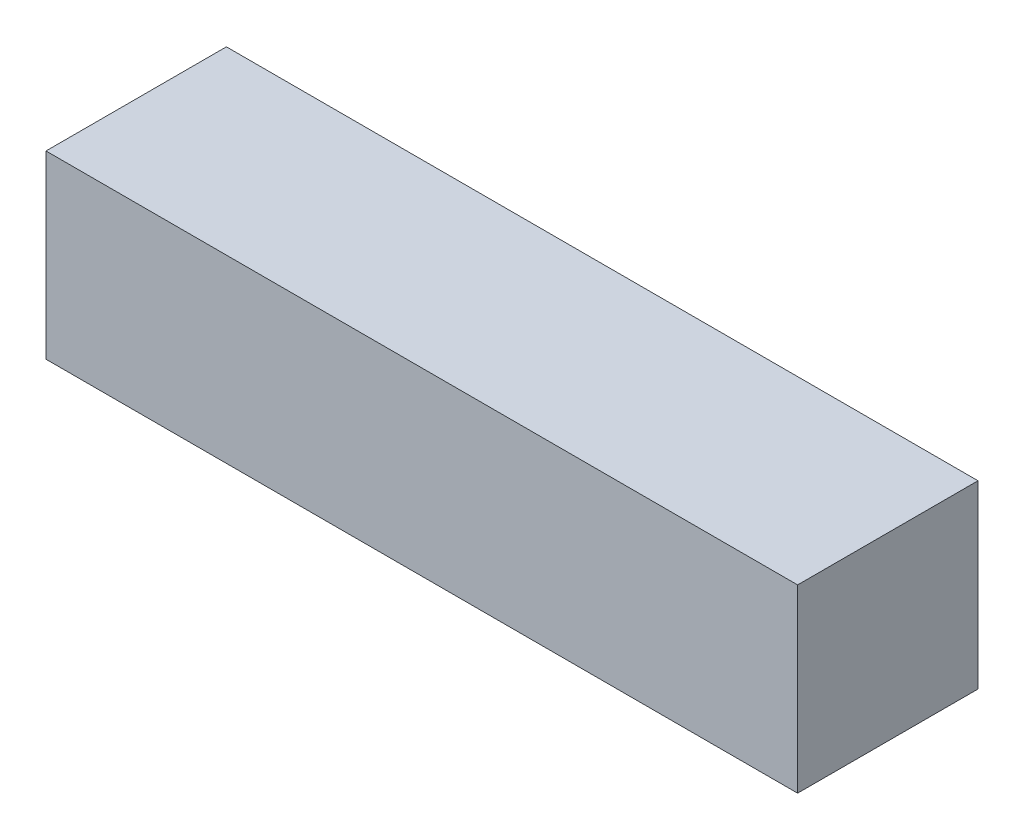
SolidWorks part; units mm, degrees
ref_plane "Front Plane" through (0, 0, 0) normal (0, 0, 1) x (1, 0, 0)
ref_plane "Top Plane" through (0, 0, 0) normal (0, 1, 0) x (1, 0, 0)
ref_plane "Right Plane" through (0, 0, 0) normal (1, 0, 0) x (0, 0, -1)
sketch "Sketch1" plane through (0, 0, 0) normal (0, 1, 0) x (1, 0, 0)
  line L1 (0, 0) -> (125, 0)
  line L2 (0, 0) -> (0, 30)
  line L3 (0, 30) -> (125, 30)
  line L4 (125, 0) -> (125, 30)
  dimension "D1" = 30
  dimension "D2" = 125
extrude "Boss-Extrude1" add sketch "Sketch1" along normal blind 30
